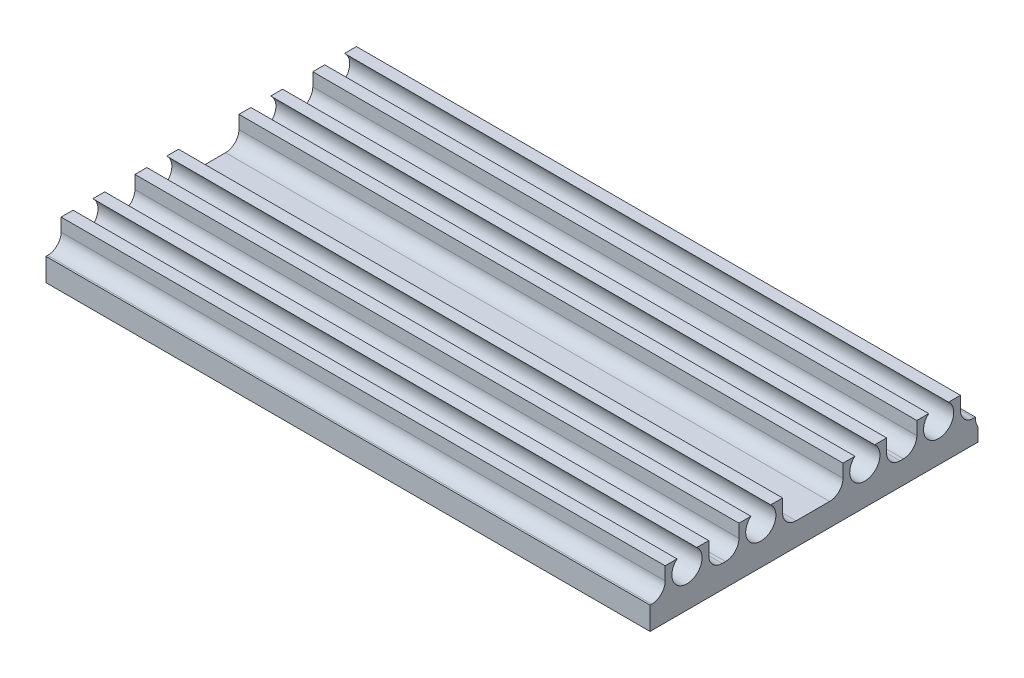
SolidWorks part; units mm, degrees
ref_plane "Спереди" through (0, 0, 0) normal (0, 0, 1) x (1, 0, 0)
ref_plane "Сверху" through (0, 0, 0) normal (0, 1, 0) x (1, 0, 0)
ref_plane "Справа" through (0, 0, 0) normal (1, 0, 0) x (0, 0, -1)
ref_plane "Плоскость4" through (90, 0, 0) normal (1, 0, 0) x (0, 0, -1)
sketch "Эскиз1" plane through (90, 0, 0) normal (1, 0, 0) x (0, 0, -1)
  line L0 (6.75, 225.9062) -> (6.75, 320.75)
  line L1 (6.75, 320.75) -> (-38.0938, 320.75)
  line L2 (-38.0938, 318.25) -> (-37.5, 318.25)
  line L3 (-37.5, 318.25) -> (-37.5, 284.75)
  line L4 (-37.5, 284.75) -> (-38.0938, 284.75)
  line L5 (-38.0938, 282.25) -> (-37.5, 282.25)
  line L6 (-37.5, 282.25) -> (-37.5, 269.25)
  line L7 (-37.5, 269.25) -> (-38.0938, 269.25)
  line L8 (-38.0938, 266.75) -> (-37.5, 266.75)
  line L9 (-37.5, 266.75) -> (-37.5, 233.25)
  line L10 (-37.5, 233.25) -> (-38.0938, 233.25)
  line L11 (-38.0938, 230.75) -> (-37.5, 230.75)
  line L12 (-37.5, 230.75) -> (-37.5, 226.5)
  line L13 (-37.5, 226.5) -> (-33.25, 226.5)
  line L14 (-33.25, 226.5) -> (-33.25, 225.9062)
  line L15 (-30.75, 225.9062) -> (-30.75, 226.5)
  line L16 (-30.75, 226.5) -> (-22.25, 226.5)
  line L17 (-22.25, 226.5) -> (-22.25, 225.9062)
  line L18 (-19.75, 225.9062) -> (-19.75, 226.5)
  line L19 (-19.75, 226.5) -> (-6.75, 226.5)
  line L20 (-6.75, 226.5) -> (-6.75, 225.9062)
  line L21 (-4.25, 225.9062) -> (-4.25, 226.5)
  line L22 (-4.25, 226.5) -> (4.25, 226.5)
  line L23 (4.25, 226.5) -> (4.25, 225.9062)
  arc A0 (-38.0938, 320.75) -> (-38.0938, 318.25) centre (-39.75, 319.5) ccw
  arc A1 (-38.0938, 284.75) -> (-38.0938, 282.25) centre (-39.75, 283.5) ccw
  arc A2 (-38.0938, 269.25) -> (-38.0938, 266.75) centre (-39.75, 268) ccw
  arc A3 (-38.0938, 233.25) -> (-38.0938, 230.75) centre (-39.75, 232) ccw
  arc A4 (-33.25, 225.9062) -> (-30.75, 225.9062) centre (-32, 224.25) ccw
  arc A5 (-22.25, 225.9062) -> (-19.75, 225.9062) centre (-21, 224.25) ccw
  arc A6 (-6.75, 225.9062) -> (-4.25, 225.9062) centre (-5.5, 224.25) ccw
  arc A7 (4.25, 225.9062) -> (6.75, 225.9062) centre (5.5, 224.25) ccw
extrude "Бобышка-Вытянуть1" add sketch "Эскиз1" against normal blind 90
sketch "Эскиз2" plane through (0, 320.75, 0) normal (0, 1, 0) x (-1, 0, 0)
  line L0 (-90, -6.75) -> (-90, 37.5)
  line L1 (-90, 37.5) -> (0, 37.5)
  line L2 (0, 37.5) -> (0, -6.75)
  line L3 (0, -6.75) -> (-90, -6.75)
extrude "Бобышка-Вытянуть2" add sketch "Эскиз2" along normal blind 8.2
sketch "Эскиз3" plane through (0, 0, -6.75) normal (0, 0, -1) x (-1, 0, 0)
  line L0 (-90, 226.5) -> (-90, 328.95)
  line L1 (-90, 328.95) -> (0, 328.95)
  line L2 (0, 328.95) -> (0, 226.5)
  line L3 (0, 226.5) -> (-90, 226.5)
extrude "Бобышка-Вытянуть3" add sketch "Эскиз3" along normal blind 8.2
sketch "Эскиз4" plane through (0, 0, 0) normal (-1, 0, 0) x (0, 0, 1)
  line L0 (24.25, 328.95) -> (24.25, 325)
  line L1 (24.25, 325) -> (28.75, 325)
  line L2 (28.75, 325) -> (28.75, 328.95)
  line L3 (28.75, 328.95) -> (24.25, 328.95)
extrude "Вырез-Вытянуть1" cut sketch "Эскиз4" against normal through all
sketch "Эскиз5" plane through (0, 0, 0) normal (-1, 0, 0) x (0, 0, 1)
  line L0 (37.5, 328.95) -> (35.25, 328.95)
  line L1 (35.25, 328.95) -> (35.25, 325)
  line L2 (35.25, 325) -> (37.5, 325)
  line L3 (37.5, 325) -> (37.5, 328.95)
extrude "Вырез-Вытянуть2" cut sketch "Эскиз5" against normal through all
sketch "Эскиз6" plane through (0, 0, 0) normal (-1, 0, 0) x (0, 0, 1)
  line L0 (-14.95, 226.5) -> (-11, 226.5)
  line L1 (-11, 226.5) -> (-11, 228.75)
  line L2 (-11, 228.75) -> (-14.95, 228.75)
  line L3 (-14.95, 228.75) -> (-14.95, 226.5)
extrude "Вырез-Вытянуть3" cut sketch "Эскиз6" against normal through all
sketch "Эскиз7" plane through (0, 0, 0) normal (-1, 0, 0) x (0, 0, 1)
  line L0 (-14.95, 235.25) -> (-11, 235.25)
  line L1 (-11, 235.25) -> (-11, 264.75)
  line L2 (-11, 264.75) -> (-14.95, 264.75)
  line L3 (-14.95, 264.75) -> (-14.95, 235.25)
extrude "Вырез-Вытянуть4" cut sketch "Эскиз7" against normal through all
sketch "Эскиз8" plane through (0, 0, 0) normal (-1, 0, 0) x (0, 0, 1)
  line L0 (-14.95, 271.25) -> (-11, 271.25)
  line L1 (-11, 271.25) -> (-11, 280.25)
  line L2 (-11, 280.25) -> (-14.95, 280.25)
  line L3 (-14.95, 280.25) -> (-14.95, 271.25)
extrude "Вырез-Вытянуть5" cut sketch "Эскиз8" against normal through all
sketch "Эскиз9" plane through (0, 0, 0) normal (-1, 0, 0) x (0, 0, 1)
  line L0 (-14.95, 286.75) -> (-11, 286.75)
  line L1 (-11, 286.75) -> (-11, 316.25)
  line L2 (-11, 316.25) -> (-14.95, 316.25)
  line L3 (-14.95, 316.25) -> (-14.95, 286.75)
extrude "Вырез-Вытянуть6" cut sketch "Эскиз9" against normal through all
sketch "Эскиз10" plane through (0, 0, 0) normal (-1, 0, 0) x (0, 0, 1)
  line L0 (-14.95, 328.95) -> (-14.95, 322.75)
  line L1 (-14.95, 322.75) -> (-11, 322.75)
  line L2 (-11, 322.75) -> (-11, 328.95)
  line L3 (-11, 328.95) -> (-14.95, 328.95)
extrude "Вырез-Вытянуть7" cut sketch "Эскиз10" against normal through all
sketch "Эскиз11" plane through (0, 0, 0) normal (-1, 0, 0) x (0, 0, 1)
  line L0 (-11, 328.95) -> (-11, 325)
  line L1 (-11, 325) -> (-8.75, 325)
  line L2 (-8.75, 325) -> (-8.75, 328.95)
  line L3 (-8.75, 328.95) -> (-11, 328.95)
extrude "Вырез-Вытянуть8" cut sketch "Эскиз11" against normal through all
sketch "Эскиз12" plane through (0, 0, 0) normal (-1, 0, 0) x (0, 0, 1)
  line L0 (-2.25, 328.95) -> (-2.25, 325)
  line L1 (-2.25, 325) -> (2.25, 325)
  line L2 (2.25, 325) -> (2.25, 328.95)
  line L3 (2.25, 328.95) -> (-2.25, 328.95)
extrude "Вырез-Вытянуть9" cut sketch "Эскиз12" against normal through all
sketch "Эскиз13" plane through (0, 0, 0) normal (-1, 0, 0) x (0, 0, 1)
  line L0 (8.75, 328.95) -> (8.75, 325)
  line L1 (8.75, 325) -> (17.75, 325)
  line L2 (17.75, 325) -> (17.75, 328.95)
  line L3 (17.75, 328.95) -> (8.75, 328.95)
extrude "Вырез-Вытянуть10" cut sketch "Эскиз13" against normal through all
sketch "Эскиз14" plane through (90, 0, 0) normal (1, 0, 0) x (0, 0, -1)
  line L0 (9.6, 323.6) -> (-36.1, 323.6)
  line L1 (-36.1, 323.6) -> (-36.1, 227.9)
  line L2 (-36.1, 227.9) -> (9.6, 227.9)
  line L3 (9.6, 227.9) -> (9.6, 323.6)
extrude "Вырез-Вытянуть11" cut sketch "Эскиз14" against normal blind 86
hole_wizard "Диаметр отверстия Ø2.5 (2.5)1" positions "Эскиз16" profile "Эскиз15" hole size "Ø2.5" standard "Ansi Metric"
sketch "Эскиз16" plane through (90, 0, 0) normal (1, 0, 0) x (0, 0, -1)
  point P0 (-39.75, 232)
  point P1 (-21, 224.25)
  point P2 (-39.75, 283.5)
  point P3 (-5.5, 224.25)
  point P4 (5.5, 224.25)
  point P5 (-39.75, 319.5)
  point P6 (-39.75, 268)
  point P7 (-32, 224.25)
sketch "Эскиз15" plane through (90, 232, 39.75) normal (0, 1, 0) x (0, 0, -1)
  line L0 (0, 0) -> (0, 90)
  line L1 (0, 90) -> (1.25, 90)
  line L2 (1.25, 90) -> (1.25, 0)
  line L5 (1.25, 0) -> (0, 0)
  line L11 (0, -6.35) -> (0, 107.95) construction
  dimension "Диаметр сквозного отверстия" = 2.5
  dimension "Глубина сквозного отверстия" = 90
hole_wizard "Диаметр отверстия Ø4.5 (4.5)1" positions "Эскиз18" profile "Эскиз17" hole size "Ø4.5" standard "Ansi Metric"
sketch "Эскиз18" plane through (0, 0, 0) normal (-1, 0, 0) x (0, 0, 1)
  point P0 (21, 327.25)
  point P1 (32, 327.25)
  point P2 (-13.25, 232)
  point P3 (-13.25, 268)
  point P4 (-13.25, 283.5)
  point P5 (-13.25, 319.5)
  point P6 (-5.5, 327.25)
  point P7 (5.5, 327.25)
sketch "Эскиз17" plane through (0, 327.25, 21) normal (0, 1, 0) x (0, 0, 1)
  line L0 (0, 0) -> (0, 90)
  line L1 (0, 90) -> (2.25, 90)
  line L2 (2.25, 90) -> (2.25, 0)
  line L5 (2.25, 0) -> (0, 0)
  line L11 (0, -6.35) -> (0, 107.95) construction
  dimension "Диаметр сквозного отверстия" = 4.5
  dimension "Глубина сквозного отверстия" = 90
hole_wizard "Диаметр отверстия Ø8.3 (8.3)1" positions "Эскиз20" profile "Эскиз19" hole size "Ø8.3" standard "Ansi Metric"
sketch "Эскиз20" plane through (0, 0, 0) normal (-1, 0, 0) x (0, 0, 1)
  point P0 (13.25, 275.75)
sketch "Эскиз19" plane through (0, 275.75, 13.25) normal (0, 1, 0) x (0, 0, 1)
  line L0 (0, 0) -> (0, 3.2)
  line L1 (0, 3.2) -> (4.15, 3.2)
  line L2 (4.15, 3.2) -> (4.15, 0)
  line L5 (4.15, 0) -> (0, 0)
  line L10 (0, 3.2) -> (-4.15, 3.2) construction
  line L11 (0, -6.35) -> (0, 107.95) construction
  dimension "Диаметр отверстия" = 8.3
  dimension "Глубина отверстия" = 3.2
  dimension "Угол заточки сверла" = 180
sketch "Эскиз21" plane through (0, 0, 0) normal (-1, 0, 0) x (0, 0, 1)
  circle A0 centre (13.25, 275.75) radius 4.15
extrude "Вырез-Вытянуть12" cut sketch "Эскиз21" against normal blind 10
sketch "Эскиз22" plane through (90, 0, 0) normal (1, 0, 0) x (0, 0, -1)
  circle A0 centre (-39.75, 319.5) radius 1.6316
  circle A1 centre (-39.75, 283.5) radius 1.5194
  circle A2 centre (-39.75, 268) radius 1.4876
  circle A3 centre (-39.75, 232) radius 1.5817
  circle A4 centre (-32, 224.25) radius 1.4878
  circle A5 centre (-21, 224.25) radius 1.426
  circle A6 centre (-5.5, 224.25) radius 1.6281
  circle A7 centre (5.5, 224.25) radius 1.5237
extrude "Бобышка-Вытянуть4" add sketch "Эскиз22" against normal blind 90
fillet "Скругление1" radius 2 1 edges at (4, 275.75, -9.6)
fillet "Скругление2" radius 2 1 edges at (4, 275.75, 36.1)
fillet "Скругление3" radius 2 3 edges at (4, 323.6, 13.25) (4.5858, 323.6, -9.0142) (4.5858, 323.6, 35.5142)
fillet "Скругление4" radius 2 3 edges at (4.5858, 227.9, -9.0142) (4, 227.9, 13.25) (4.5858, 227.9, 35.5142)
fillet "Скругление5" radius 2 1 edges at (45, 325, 35.25)
fillet "Скругление6" radius 2 1 edges at (45, 325, 28.75)
fillet "Скругление7" radius 2 1 edges at (45, 325, 24.25)
fillet "Скругление8" radius 2 1 edges at (45, 325, 17.75)
fillet "Скругление9" radius 2 1 edges at (45, 325, 8.75)
fillet "Скругление10" radius 2 1 edges at (45, 325, 2.25)
fillet "Скругление11" radius 2 1 edges at (45, 325, -2.25)
fillet "Скругление12" radius 2 1 edges at (45, 325, -8.75)
fillet "Скругление13" radius 2 1 edges at (45, 322.75, -11)
fillet "Скругление14" radius 2 1 edges at (45, 316.25, -11)
fillet "Скругление15" radius 2 1 edges at (45, 286.75, -11)
fillet "Скругление16" radius 2 1 edges at (45, 280.25, -11)
fillet "Скругление17" radius 2 1 edges at (45, 271.25, -11)
fillet "Скругление18" radius 2 1 edges at (45, 264.75, -11)
fillet "Скругление19" radius 2 1 edges at (45, 235.25, -11)
fillet "Скругление20" radius 2 1 edges at (45, 228.75, -11)
sketch "Эскиз23" plane through (90, 0, 0) normal (1, 0, 0) x (0, 0, -1)
  line L0 (-36.1, 323.6) -> (9.6, 323.6) construction
  line L1 (-36.1, 323.6) -> (9.6, 323.6)
  line L2 (-36.1, 323.6) -> (-56.6819, 323.6)
  line L3 (-56.6819, 323.6) -> (-56.6819, 211.9176)
  line L4 (-56.6819, 211.9176) -> (38.9456, 211.9176)
  line L5 (38.9456, 211.9176) -> (38.9456, 323.6)
  line L6 (38.9456, 323.6) -> (9.6, 323.6)
extrude "Вырез-Вытянуть13" cut sketch "Эскиз23" against normal blind 96
sketch "Эскиз24" plane through (0, 323.6, 0) normal (0, -1, 0) x (1, 0, 0)
  line L4 (0, -11.3637) -> (90, -11.3637)
  line L5 (90, -11.3637) -> (90, 37.5)
  line L6 (90, 37.5) -> (0, 37.5)
  line L7 (0, 37.5) -> (0, -11.3637)
  line L8 (0, -11.3637) -> (90, -11.3637)
  line L9 (90, -11.3637) -> (90, 37.5)
  line L10 (90, 37.5) -> (0, 37.5)
  line L11 (0, 37.5) -> (0, -11.3637)
  dimension "D1" = 0
extrude "Бобышка-Вытянуть5" add sketch "Эскиз24" along normal blind 2
